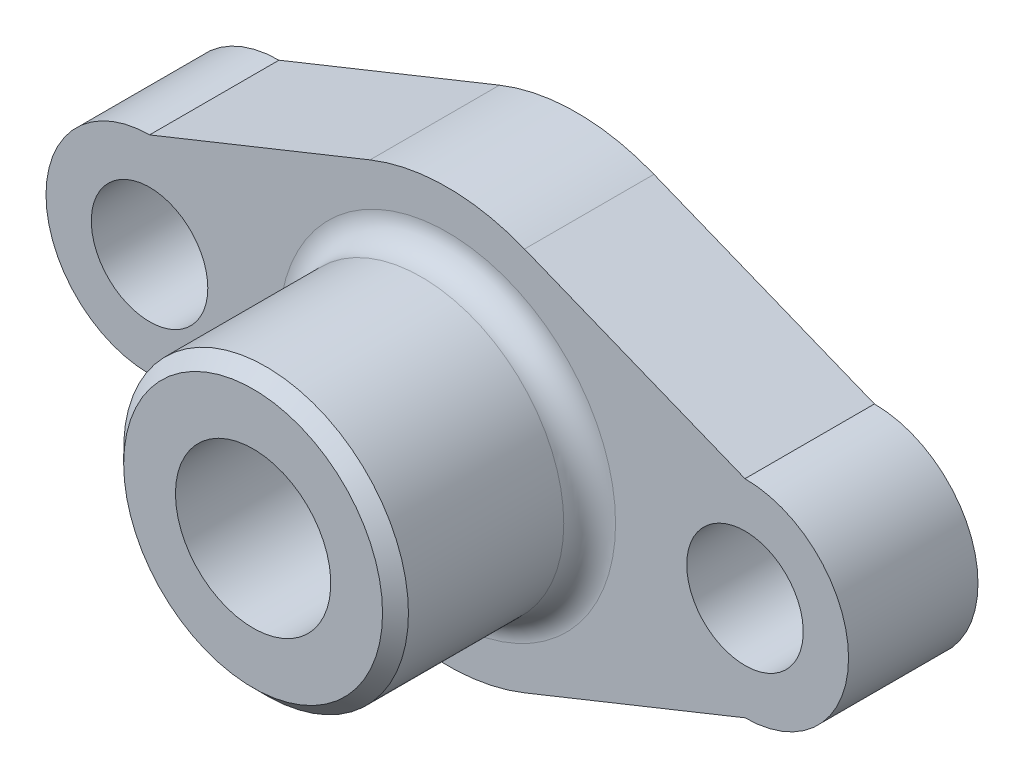
SolidWorks part; units mm, degrees
ref_plane "Спереди" through (0, 0, 0) normal (0, 0, 1) x (1, 0, 0)
ref_plane "Сверху" through (0, 0, 0) normal (0, 1, 0) x (1, 0, 0)
ref_plane "Справа" through (0, 0, 0) normal (1, 0, 0) x (0, 0, -1)
other "Configuration Table"
sketch "Эскиз1" plane through (0, 0, 0) normal (0, 0, 1) x (1, 0, 0)
  line L0 (197.5051, 0) -> (-205.4079, 0) construction
  line L1 (0, 262.7953) -> (0, -280.8171) construction
  line L2 (-23, 8) -> (-5.9667, 14.8458)
  line L3 (-23, -8) -> (-5.9667, -14.8458)
  line L4 (23, -8) -> (5.9667, -14.8458)
  line L5 (23, 8) -> (5.9667, 14.8458)
  arc A0 (-5.9667, -14.8458) -> (5.9667, -14.8458) centre (0, 0) ccw
  arc A2 (-23, 8) -> (-23, -8) centre (-23, 0) ccw
  circle A3 centre (-23, 0) radius 4.5
  arc A4 (5.9667, -14.8458) -> (-5.9667, -14.8458) centre (0, 0) cw construction
  circle A5 centre (23, 0) radius 4.5
  arc A6 (23, 8) -> (23, -8) centre (23, 0) cw
  arc A7 (5.9667, 14.8458) -> (-5.9667, 14.8458) centre (0, 0) ccw
  arc A8 (-16, 0) -> (5.9667, 14.8458) centre (0, 0) cw construction
  dimension "D1" = 32
  dimension "D2" = 16
  dimension "D3" = 9
  dimension "D4" = 46
extrude "Бобышка-Вытянуть1" add sketch "Эскиз1" along normal blind 10
sketch "Эскиз4" plane through (0, 0, 0) normal (0, 0, 1) x (1, 0, 0)
  circle A0 centre (0, 0) radius 11
  dimension "D1" = 22
extrude "Бобышка-Вытянуть2" add sketch "Эскиз4" along normal blind 25
sketch "Эскиз5" plane through (0, 0, 0) normal (0, 1, 0) x (1, 0, 0)
  line L0 (0, 38.3453) -> (0, -53.3896) construction
  line L1 (0, 0) -> (-10, 0)
  line L2 (-5.9667, 0) -> (-23, 0) construction
  line L3 (-10, 0) -> (-8.1227, -13.1414)
  line L4 (-7.1327, -14) -> (-6, -14)
  line L5 (-6, -14) -> (-6, -25)
  line L6 (-11, -25) -> (11, -25) construction
  line L7 (-6, -25) -> (0, -25)
  line L8 (0, 0) -> (0, -25)
  arc A0 (-8.1227, -13.1414) -> (-7.1327, -14) centre (-7.1327, -13) ccw
  point P15 (-8, -14)
  dimension "D5" = 1
  dimension "D1" = 14
  dimension "D2" = 12
  dimension "D3" = 20
  dimension "D4" = 16
revolve "Вырез-Повернуть1" cut sketch "Эскиз5" angle 360 about L0
fillet "Скругление1" radius 2 1 edges at (11, 0, 10)
chamfer "Фаска1" distance 1 angle 45 1 edges at (11, 0, 25)
